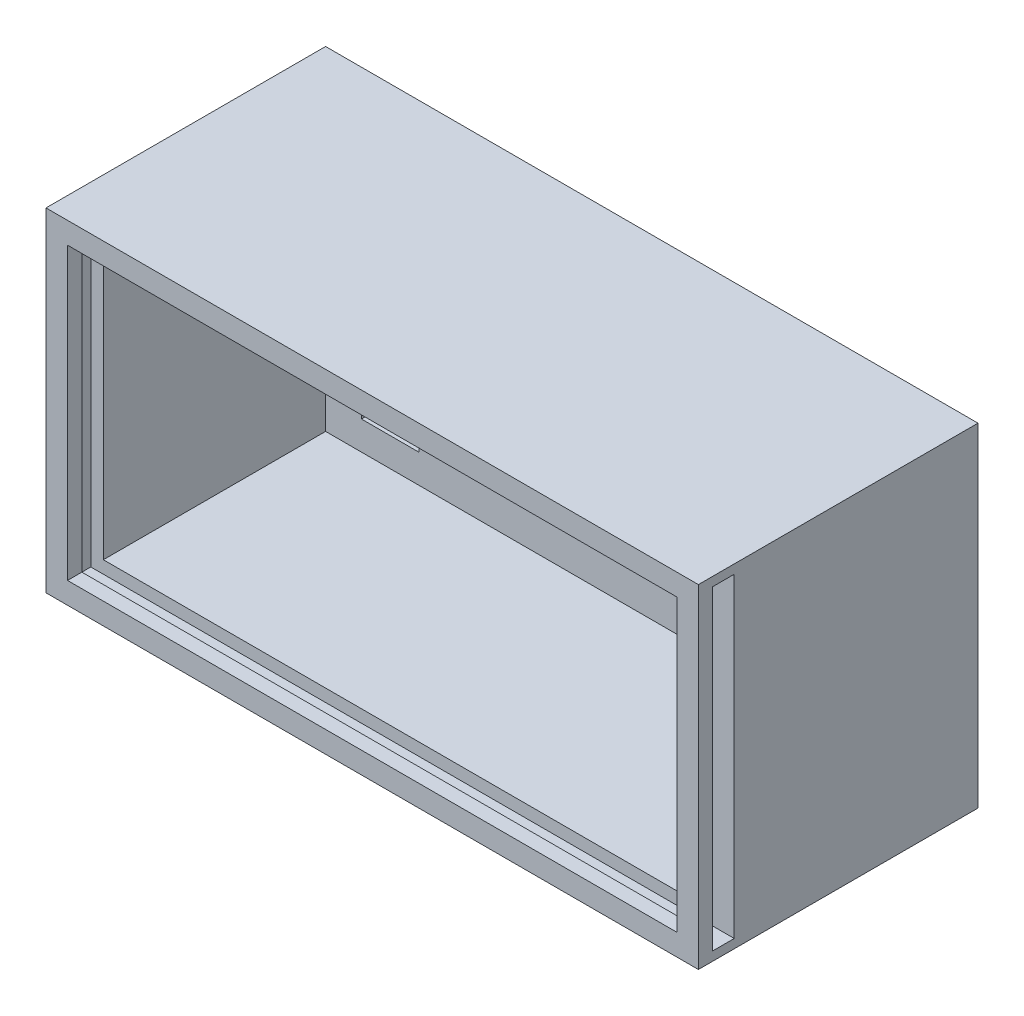
SolidWorks part; units mm, degrees
ref_plane "前基準面" through (0, 0, 0) normal (0, 0, 1) x (1, 0, 0)
ref_plane "上基準面" through (0, 0, 0) normal (0, 1, 0) x (1, 0, 0)
ref_plane "右基準面" through (0, 0, 0) normal (1, 0, 0) x (0, 0, -1)
sketch "草圖1" plane through (0, 0, 0) normal (0, 0, 1) x (1, 0, 0)
  line L0 (0, -55) -> (0, 55) construction
  line L1 (-42.5, 20.25) -> (42.5, 20.25)
  line L2 (-42.5, 20.25) -> (-42.5, -20.25)
  line L3 (-42.5, -20.25) -> (42.5, -20.25)
  line L4 (42.5, 20.25) -> (42.5, -20.25)
  line L5 (55, 0) -> (-55, 0) construction
  line L6 (-42.5, 0) -> (-45.5, 0) construction
  line L7 (45.5, 23.25) -> (-45.5, 23.25)
  line L8 (45.5, 23.25) -> (45.5, -23.25)
  line L9 (45.5, -23.25) -> (-45.5, -23.25)
  line L10 (-45.5, 23.25) -> (-45.5, -23.25)
  line L11 (0, -23.25) -> (0, -20.25) construction
  line L12 (45.5, 0) -> (42.5, 0) construction
  line L13 (0, 20.25) -> (0, 23.25) construction
  point P8 (0, 0)
  dimension "D1" = 85
  dimension "D2" = 40.5
  dimension "D3" = 91
  dimension "D4" = 46.5
  dimension "D5" = 3
  dimension "D6" = 3
  dimension "D7" = 0
  dimension "D8" = 0
extrude "填料-伸長1" add sketch "草圖1" along normal blind 36
sketch "草圖2" plane through (0, 0, 0) normal (0, 0, -1) x (-1, 0, 0)
  line L1 (-45.5, 23.25) -> (45.5, 23.25)
  line L2 (-45.5, 23.25) -> (-45.5, -23.25)
  line L3 (-45.5, -23.25) -> (45.5, -23.25)
  line L4 (45.5, 23.25) -> (45.5, -23.25)
extrude "填料-伸長2" add sketch "草圖2" along normal blind 3
ref_plane "平面1" through (0, 0, 31) normal (0, 0, 1) x (1, 0, 0)
sketch "草圖3" plane through (0, 0, 31) normal (0, 0, 1) x (1, 0, 0)
  line L0 (45.5, 23.25) -> (-45.5, 23.25) construction
  line L1 (-44.25, 22) -> (45.75, 22)
  line L2 (-44.25, 22) -> (-44.25, -22)
  line L3 (-44.25, -22) -> (45.75, -22)
  line L4 (45.75, 22) -> (45.75, -22)
  line L6 (-45.5, -23.25) -> (45.5, -23.25) construction
  line L7 (-45.5, 23.25) -> (-45.5, -23.25) construction
  dimension "D1" = 1.25
  dimension "D2" = 1.25
  dimension "D3" = 1.25
  dimension "D4" = 90
  dimension "D5" = 44
extrude "除料-伸長1" cut sketch "草圖3" along normal blind 3
sketch "草圖4" plane through (0, 0, -3) normal (0, 0, -1) x (-1, 0, 0)
  line L0 (45.5, -23.25) -> (45.5, 23.25) construction
  line L1 (29.5, -4.25) -> (37.5, -4.25)
  line L2 (29.5, -4.25) -> (29.5, -16.25)
  line L3 (29.5, -16.25) -> (37.5, -16.25)
  line L4 (37.5, -4.25) -> (37.5, -16.25)
  line L5 (-45.5, -23.25) -> (45.5, -23.25) construction
  line L6 (45.5, 23.25) -> (-45.5, 23.25) construction
  line L7 (-40.1486, 17.25) -> (-35.1486, 17.25)
  line L8 (-40.1486, 17.25) -> (-40.1486, 9.25)
  line L9 (-40.1486, 9.25) -> (-35.1486, 9.25)
  line L10 (-35.1486, 17.25) -> (-35.1486, 9.25)
  dimension "D1" = 8
  dimension "D2" = 12
  dimension "D3" = 8
  dimension "D4" = 7
  dimension "D5" = 5
  dimension "D6" = 8
  dimension "D7" = 6
extrude "除料-伸長2" cut sketch "草圖4" against normal blind 10
